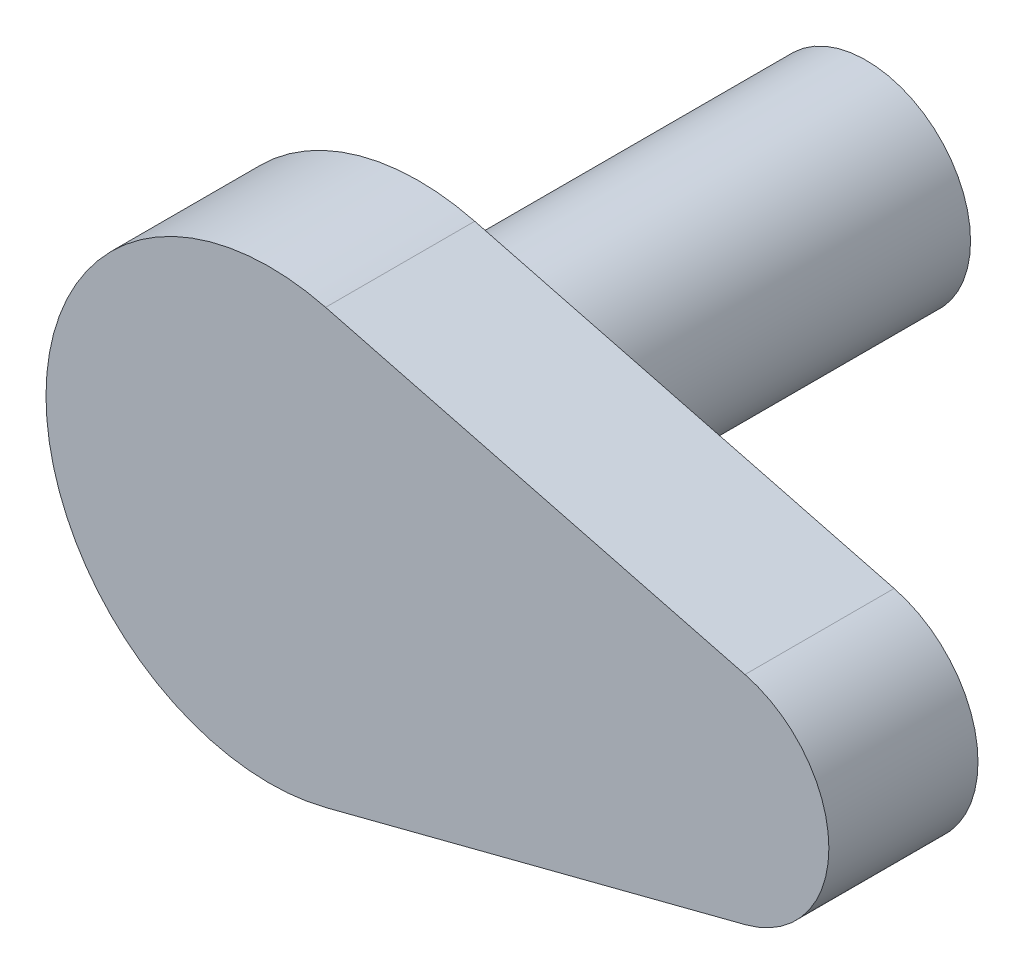
SolidWorks part; units mm, degrees
ref_plane "Front Plane" through (0, 0, 0) normal (0, 0, 1) x (1, 0, 0)
ref_plane "Top Plane" through (0, 0, 0) normal (0, 1, 0) x (1, 0, 0)
ref_plane "Right Plane" through (0, 0, 0) normal (1, 0, 0) x (0, 0, -1)
sketch "Sketch1" plane through (0, 0, 0) normal (0, 0, 1) x (1, 0, 0)
  circle A0 centre (0, 0) radius 7
  dimension "D1" = 14
extrude "Boss-Extrude1" add sketch "Sketch1" along normal blind 30
sketch "Sketch2" plane through (0, 0, 30) normal (0, 0, 1) x (1, 0, 0)
  line L0 (3.75, 14.5237) -> (31.875, 7.2618)
  line L1 (31.875, -7.2618) -> (3.75, -14.5237)
  arc A0 (31.875, 7.2618) -> (31.875, -7.2618) centre (30, 0) cw
  arc A1 (3.75, -14.5237) -> (3.75, 14.5237) centre (0, 0) cw
  point P6 (0, 0)
  point P8 (0, 0)
  dimension "D1" = 7.5
  dimension "D2" = 15
  dimension "D3" = 30
extrude "Boss-Extrude2" add sketch "Sketch2" along normal blind 10
